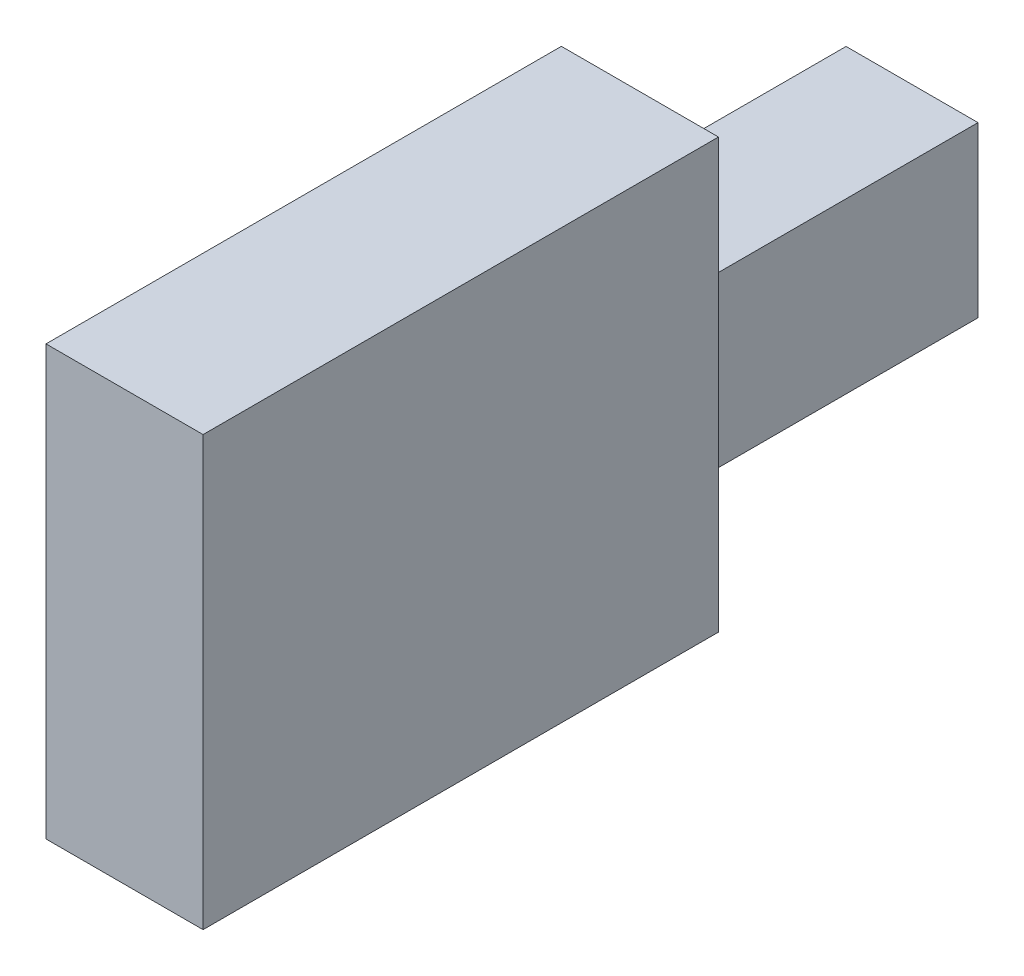
SolidWorks part; units mm, degrees
ref_plane "Front Plane" through (0, 0, 0) normal (0, 0, 1) x (1, 0, 0)
ref_plane "Top Plane" through (0, 0, 0) normal (0, 1, 0) x (1, 0, 0)
ref_plane "Right Plane" through (0, 0, 0) normal (1, 0, 0) x (0, 0, -1)
sketch "Sketch1" plane through (0, 0, 0) normal (0, 0, 1) x (1, 0, 0)
  line L1 (-1.6, -2.05) -> (1.6, -2.05)
  line L2 (-1.6, -2.05) -> (-1.6, 2.05)
  line L3 (-1.6, 2.05) -> (1.6, 2.05)
  line L4 (1.6, -2.05) -> (1.6, 2.05)
  line L5 (-1.6, -2.05) -> (1.6, 2.05) construction
  line L6 (-1.6, 2.05) -> (1.6, -2.05) construction
  point P0 (0, 0)
  dimension "D1" = 4.1
  dimension "D2" = 3.2
extrude "Boss-Extrude1" add sketch "Sketch1" along normal blind 6.6
sketch "Sketch2" plane through (0, 0, 6.6) normal (0, 0, 1) x (1, 0, 0)
  line L1 (-1.905, 5.2) -> (1.905, 5.2)
  line L2 (-1.905, 5.2) -> (-1.905, -5.2)
  line L3 (-1.905, -5.2) -> (1.905, -5.2)
  line L4 (1.905, 5.2) -> (1.905, -5.2)
  line L5 (-1.905, 5.2) -> (1.905, -5.2) construction
  line L6 (-1.905, -5.2) -> (1.905, 5.2) construction
  point P0 (0, 0)
  dimension "D1" = 10.4
  dimension "D2" = 3.81
extrude "Boss-Extrude2" add sketch "Sketch2" along normal blind 12.5
